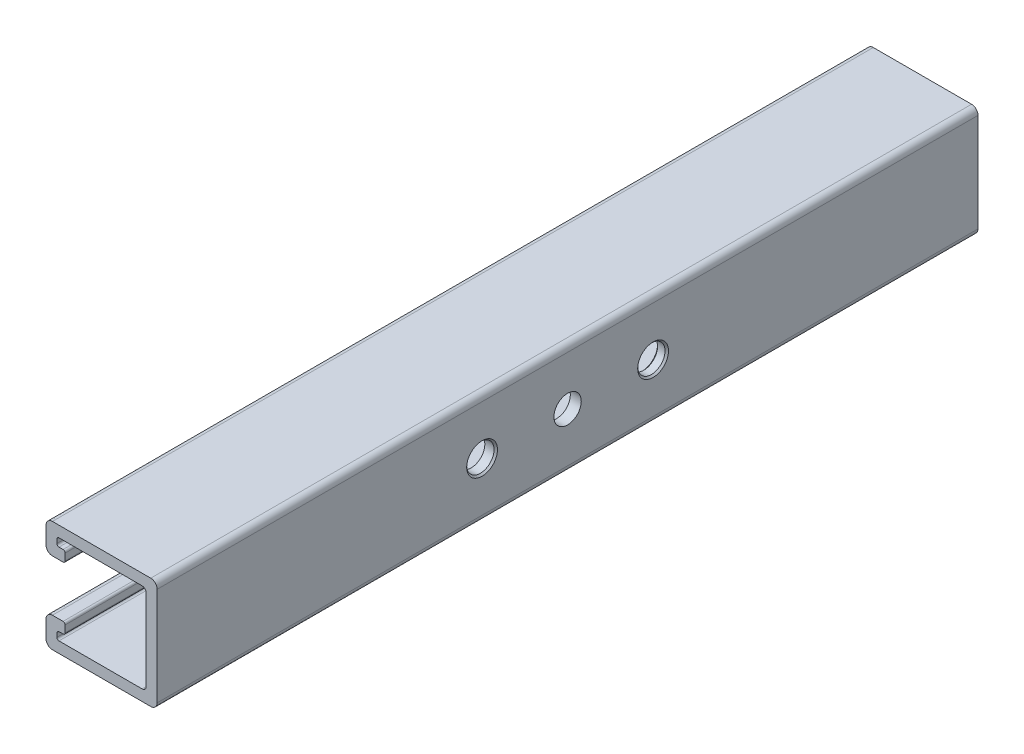
SolidWorks part; units mm, degrees
material "S-Glass Fiber"
ref_plane "Front Plane" through (0, 0, 0) normal (0, 0, 1) x (1, 0, 0)
ref_plane "Top Plane" through (0, 0, 0) normal (0, 1, 0) x (1, 0, 0)
ref_plane "Right Plane" through (0, 0, 0) normal (1, 0, 0) x (0, 0, -1)
sketch "Sketch1" plane through (0, 0, 0) normal (0, 0, 1) x (1, 0, 0)
  line L0 (-13.5255, 9.525) -> (-18.2499, 9.525)
  line L1 (-20.6375, 11.9126) -> (-20.6375, 18.2499)
  line L2 (-18.2499, 20.6375) -> (18.2499, 20.6375)
  line L3 (20.6375, 18.2499) -> (20.6375, -18.2499)
  line L4 (18.2499, -20.6375) -> (-18.2499, -20.6375)
  line L5 (-20.6375, -18.2499) -> (-20.6375, -11.9126)
  line L6 (-18.2499, -9.525) -> (-13.5255, -9.525)
  line L7 (0, 0) -> (20.6375, 0) construction
  line L8 (0, 0) -> (0, 20.6375) construction
  arc A0 (-20.6375, 18.2499) -> (-18.2499, 20.6375) centre (-18.2499, 18.2499) cw
  arc A1 (-18.2499, 9.525) -> (-20.6375, 11.9126) centre (-18.2499, 11.9126) cw
  arc A2 (-20.6375, -11.9126) -> (-18.2499, -9.525) centre (-18.2499, -11.9126) cw
  arc A3 (-18.2499, -20.6375) -> (-20.6375, -18.2499) centre (-18.2499, -18.2499) cw
  arc A4 (20.6375, -18.2499) -> (18.2499, -20.6375) centre (18.2499, -18.2499) cw
  arc A5 (18.2499, 20.6375) -> (20.6375, 18.2499) centre (18.2499, 18.2499) cw
  point P14 (-20.6375, 20.6375)
  point P23 (20.6375, -20.6375)
  point P26 (20.6375, 20.6375)
  dimension "D4" = 2.3876
  dimension "D1" = 41.275
  dimension "D2" = 41.275
  dimension "D3" = 19.05
  dimension "D5" = 7.112
extrude "Extrude-Thin1" add sketch "Sketch1" against normal blind 304.8 thin
fillet "Fillet2" radius 0.762 8 edges at (-16.5735, 13.589, -152.4) (-16.5735, -16.5735, -152.4) (-16.5735, 16.5735, -152.4) (-13.5255, 13.589, -152.4) (-13.5255, 9.525, -152.4) (-13.5255, -9.525, -152.4) (-13.5255, -13.589, -152.4) (-16.5735, -13.589, -152.4)
fillet "Fillet3" radius 1.524 2 edges at (16.5735, 16.5735, -152.4) (16.5735, -16.5735, -152.4)
sketch "Sketch3" plane through (0, 0, 0) normal (1, 0, 0) x (0, 0, -1)
  line L0 (0, 0) -> (304.8, 0) construction
  line L1 (304.8, 18.2499) -> (304.8, -18.2499) construction
  line L2 (0, 0) -> (0, 20.6375) construction
  line L3 (304.8, 0) -> (304.8, 20.6375) construction
  line L4 (304.8, 20.6375) -> (0, 20.6375) construction
  point P3 (101.6, 0)
  point P4 (203.2, 0)
  dimension "D1" = 101.6
  dimension "D2" = 101.6
sketch "Sketch4" plane through (20.6375, 0, 0) normal (1, 0, 0) x (0, 0, -1)
  line L0 (0, 0) -> (304.8, 0) construction
  line L1 (0, 18.2499) -> (0, -18.2499) construction
  line L2 (304.8, 18.2499) -> (304.8, -18.2499) construction
  line L3 (184.15, 5.08) -> (152.4, 5.08) construction
  line L4 (152.4, 5.08) -> (120.65, 5.08) construction
  circle A0 centre (152.4, 0) radius 5.08
  circle A1 centre (184.15, 0) radius 5.08
  circle A2 centre (120.65, 0) radius 5.08
  dimension "D1" = 10.16
  dimension "D2" = 10.16
  dimension "D3" = 31.75
extrude "Cut-Extrude1" cut sketch "Sketch4" against normal through all
chamfer "Chamfer1" distance 0.635 angle 45 3 edges at (20.6375, 0, -125.73) (16.5735, 0, -179.07) (20.6375, 0, -189.23)
